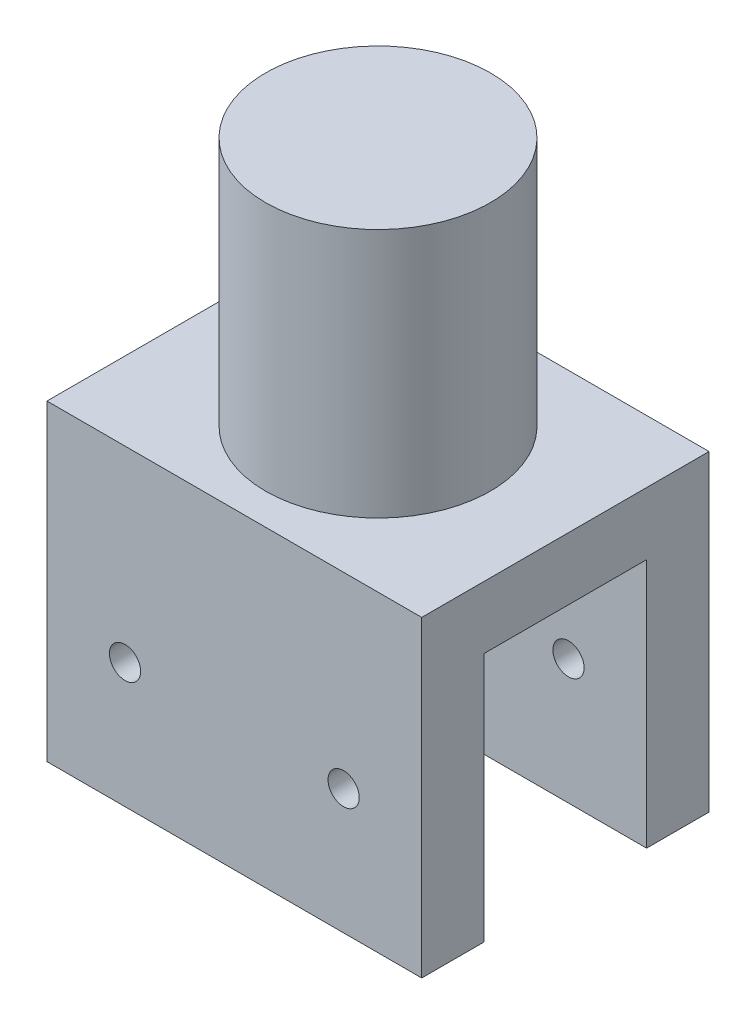
SolidWorks part; units mm, degrees
material "ABS"
ref_plane "Front Plane" through (0, 0, 0) normal (0, 0, 1) x (1, 0, 0)
ref_plane "Top Plane" through (0, 0, 0) normal (0, 1, 0) x (1, 0, 0)
ref_plane "Right Plane" through (0, 0, 0) normal (1, 0, 0) x (0, 0, -1)
sketch "Sketch1" plane through (0, 0, 0) normal (0, 1, 0) x (1, 0, 0)
  line L1 (-30, 23) -> (30, 23)
  line L2 (-30, 23) -> (-30, -23)
  line L3 (-30, -23) -> (30, -23)
  line L4 (30, 23) -> (30, -23)
  line L5 (-30, 23) -> (30, -23) construction
  line L6 (-30, -23) -> (30, 23) construction
  point P0 (0, 0)
  dimension "D1" = 46
  dimension "D2" = 60
extrude "Boss-Extrude1" add sketch "Sketch1" along normal blind 10
sketch "Sketch2" plane through (0, 0, 0) normal (0, -1, 0) x (1, 0, 0)
  line L0 (30, 23) -> (30, -23) construction
  line L1 (-30, 23) -> (30, 23)
  line L2 (-30, 23) -> (-30, 13)
  line L3 (-30, 13) -> (30, 13)
  line L4 (30, 23) -> (30, 13)
  line L6 (-30, -23) -> (30, -23)
  line L7 (-30, -23) -> (-30, -13)
  line L8 (-30, -13) -> (30, -13)
  line L9 (30, -23) -> (30, -13)
  dimension "D1" = 10
extrude "Boss-Extrude2" add sketch "Sketch2" along normal blind 40
sketch "Sketch3" plane through (0, 10, 0) normal (0, 1, 0) x (1, 0, 0)
  circle A0 centre (0, 0) radius 18
  dimension "D1" = 36
extrude "Boss-Extrude3" add sketch "Sketch3" along normal blind 40
sketch "Sketch4" plane through (0, 0, -23) normal (0, 0, -1) x (-1, 0, 0)
  line L0 (-17.5, -20) -> (17.5, -20) construction
  line L1 (0, -20) -> (0, 0) construction
  circle A0 centre (-17.5, -20) radius 2.5
  circle A1 centre (17.5, -20) radius 2.5
  dimension "D1" = 5
  dimension "D2" = 20
  dimension "D3" = 35
extrude "Cut-Extrude1" cut sketch "Sketch4" against normal through all
